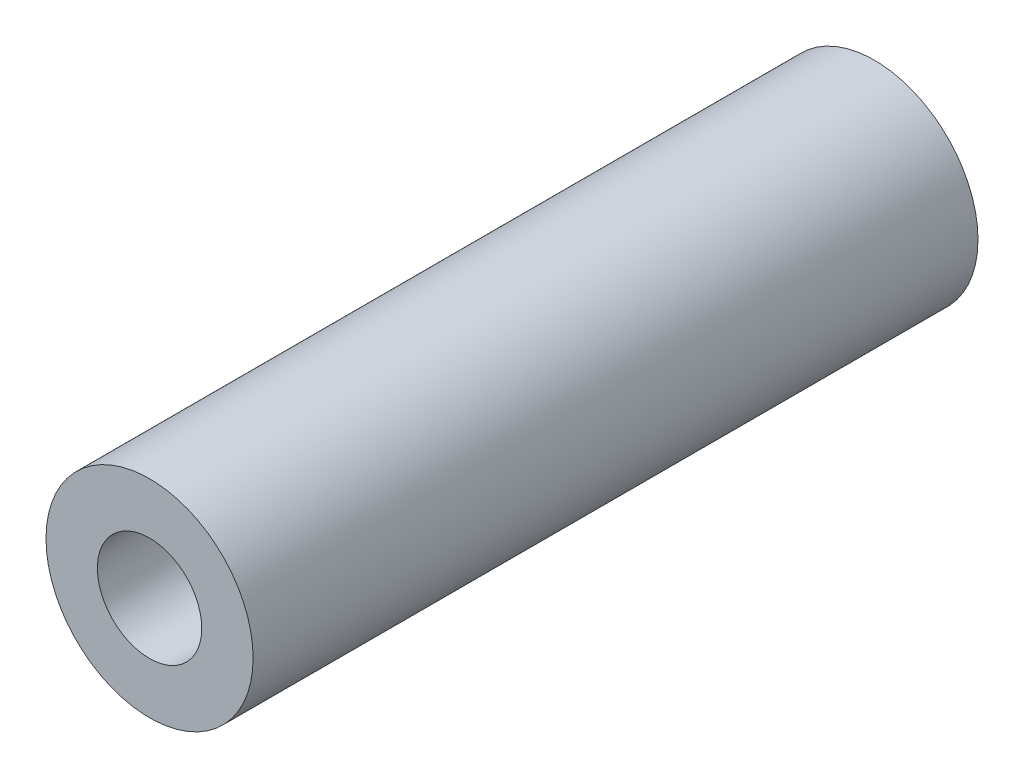
SolidWorks part; units mm, degrees
ref_plane "Front Plane" through (0, 0, 0) normal (0, 0, 1) x (1, 0, 0)
ref_plane "Top Plane" through (0, 0, 0) normal (0, 1, 0) x (1, 0, 0)
ref_plane "Right Plane" through (0, 0, 0) normal (1, 0, 0) x (0, 0, -1)
sketch "Sketch1" plane through (0, 0, 0) normal (0, 0, 1) x (1, 0, 0)
  circle A0 centre (0, 0) radius 6.35
  circle A1 centre (0, 0) radius 3.2004
  dimension "OD" = 12.7
  dimension "ID" = 6.4008
extrude "Extrude1" add sketch "Sketch1" along normal mid plane 44.45
sketch "Sketch2" plane through (0, 0, 0) normal (1, 0, 0) x (0, 0, -1)
  line L0 (-22.225, -3.2004) -> (22.225, -3.2004) construction
  line L3 (22.225, 3.2004) -> (-22.225, 3.2004) construction
  line L5 (-22.225, -3.2004) -> (22.225, -3.2004)
  line L6 (22.225, 3.2004) -> (-22.225, 3.2004)
sketch "Sketch4" plane through (0, 0, 22.225) normal (0, 0, 1) x (1, 0, 0)
  line L0 (0, 0) -> (-2.263, 2.263)
  line L1 (0, -5.2388) -> (0, 5.2388) construction
  circle A0 centre (0, 0) radius 3.2004 construction
  dimension "D1" = 45
